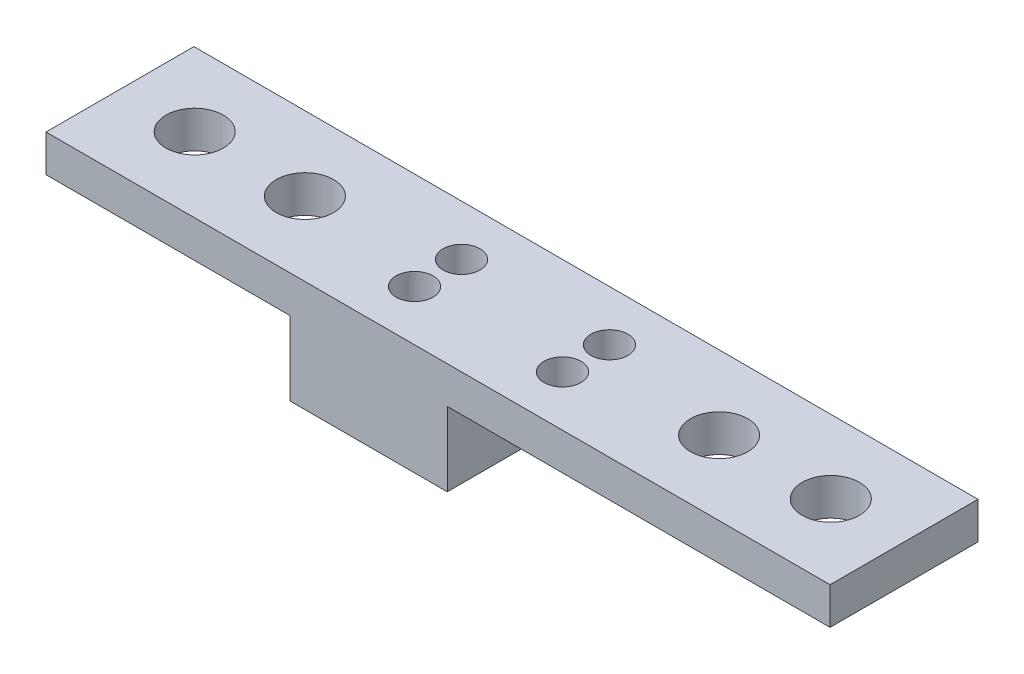
SolidWorks part; units mm, degrees
ref_plane "Front Plane" through (0, 0, 0) normal (0, 0, 1) x (1, 0, 0)
ref_plane "Top Plane" through (0, 0, 0) normal (0, 1, 0) x (1, 0, 0)
ref_plane "Right Plane" through (0, 0, 0) normal (1, 0, 0) x (0, 0, -1)
sketch "Sketch1" plane through (0, 0, 0) normal (0, 1, 0) x (1, 0, 0)
  line L0 (0, 4) -> (0, -4) construction
  line L1 (-15.2, -4) -> (15.2, -4)
  line L2 (-15.2, -4) -> (-15.2, 4)
  line L3 (-15.2, 4) -> (15.2, 4)
  line L4 (15.2, -4) -> (15.2, 4)
  line L5 (-15.2, -4) -> (15.2, 4) construction
  line L6 (-15.2, 4) -> (15.2, -4) construction
  circle A0 centre (-11.2, 0) radius 1.55
  circle A1 centre (11.2, 0) radius 1.55
  circle A2 centre (-4, 0) radius 1.27 construction
  circle A3 centre (4, 0) radius 1.27 construction
  circle A4 centre (-4, 1.27) radius 1
  circle A5 centre (-4, -1.27) radius 1
  circle A6 centre (4, 1.27) radius 1
  circle A7 centre (4, -1.27) radius 1
  circle A8 centre (-4, 0) radius 3.175 construction
  circle A9 centre (4, 0) radius 3.175 construction
  point P0 (0, 0)
  dimension "D1" = 3.1
  dimension "D4" = 2.54
  dimension "D6" = 2
  dimension "D7" = 6.35
  dimension "D2" = 22.4
  dimension "D3" = 4
  dimension "D5" = 4
  dimension "D8" = 4
extrude "Boss-Extrude1" add sketch "Sketch1" along normal blind 2
sketch "Sketch3" plane through (0, 0, 0) normal (0, -1, 0) x (1, 0, 0)
  line L0 (-15.2, 4) -> (15.2, 4) construction
  line L1 (-0.5, -4) -> (0.5, -4)
  line L2 (-0.5, -4) -> (-0.5, 4)
  line L3 (-0.5, 4) -> (0.5, 4)
  line L4 (0.5, -4) -> (0.5, 4)
  line L5 (-0.5, -4) -> (0.5, 4) construction
  line L6 (-0.5, 4) -> (0.5, -4) construction
  point P0 (0, 0)
  dimension "D1" = 1
extrude "Boss-Extrude2" add sketch "Sketch3" along normal blind 4
sketch "Sketch4" plane through (0, 0, 0) normal (0, -1, 0) x (1, 0, 0)
  line L0 (-15.2, 4) -> (-0.5, 4) construction
  line L1 (-0.5, -4) -> (-8, -4)
  line L2 (-0.5, -4) -> (-0.5, 4)
  line L3 (-0.5, 4) -> (-8, 4)
  line L4 (-8, -4) -> (-8, 4)
  line L5 (-8, 0) -> (0, 0) construction
  circle A1 centre (-4, 1.27) radius 1 construction
  circle A2 centre (-4, 1.27) radius 1
  circle A3 centre (-4, -1.27) radius 1 construction
  circle A4 centre (-4, -1.27) radius 1
  point P13 (-4, 0)
extrude "Boss-Extrude3" add sketch "Sketch4" along normal up to surface (4 mm away) up to face at (0, -4, 0)
sketch "Sketch5" plane through (0, -4, 0) normal (0, -1, 0) x (-1, 0, 0)
  circle A0 centre (-11.2, 0) radius 1.55 construction
  circle A1 centre (-11.2, 0) radius 1.55
  circle A2 centre (11.2, 0) radius 1.55 construction
  circle A3 centre (11.2, 0) radius 1.55
  circle A4 centre (11.2, 0) radius 2.7
  circle A5 centre (-11.2, 0) radius 2.7
  dimension "D1" = 5.4
sketch "Sketch6" plane through (0, 2, 0) normal (0, 1, 0) x (1, 0, 0)
  line L0 (-17.2, 0.0401) -> (-11.2, 0) construction
  line L1 (-15.2, -4) -> (-21.2, -4)
  line L2 (-15.2, -4) -> (-15.2, 4)
  line L3 (-15.2, 4) -> (-21.2, 4)
  line L4 (-21.2, -4) -> (-21.2, 4)
  line L5 (15.2, 4) -> (-15.2, 4) construction
  line L6 (0, 4) -> (0, -4) construction
  line L7 (-15.2, -4) -> (15.2, -4) construction
  line L8 (21.2, -4) -> (21.2, 4)
  line L9 (15.2, 4) -> (21.2, 4)
  line L10 (15.2, -4) -> (15.2, 4)
  line L11 (15.2, -4) -> (21.2, -4)
  circle A0 centre (-17.2, 0.0401) radius 1.55
  circle A1 centre (-11.2, 0) radius 1.55 construction
  circle A2 centre (17.2, 0.0401) radius 1.55
  point P9 (-14.2, 0.0201)
  point P25 (14.2, 0.0201)
  point P29 (-15.2, 0)
  dimension "D1" = 6
  dimension "D2" = 4
extrude "Boss-Extrude4" add sketch "Sketch6" against normal up to surface (2 mm away) up to face at (7.85, 0, 0)
